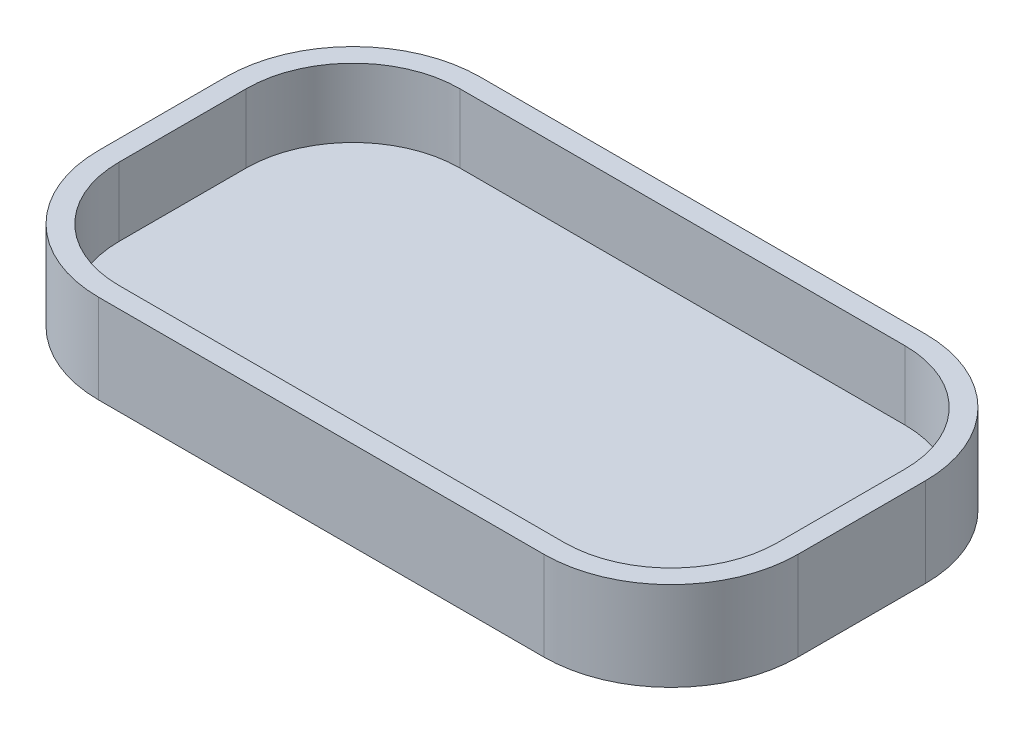
SolidWorks part; units mm, degrees
material "Kujná litina (temperovaná)"
ref_plane "Přední rovina" through (0, 0, 0) normal (0, 0, 1) x (1, 0, 0)
ref_plane "Horní rovina" through (0, 0, 0) normal (0, 1, 0) x (1, 0, 0)
ref_plane "Pravá rovina" through (0, 0, 0) normal (1, 0, 0) x (0, 0, -1)
sketch "Skica1" plane through (0, 0, 0) normal (0, 1, 0) x (1, 0, 0)
  line L1 (0, 0) -> (-55, 0)
  line L2 (0, 0) -> (0, 30)
  line L3 (0, 30) -> (-55, 30)
  line L4 (-55, 0) -> (-55, 30)
  point P7 (-52.8261, 33.8351)
  dimension "D1" = 55
  dimension "D2" = 30
extrude "Přidat vysunutím1" add sketch "Skica1" along normal blind 7
fillet "Zaoblit1" radius 10 4 edges at (0, 3.5, -30) (0, 3.5, 0) (-55, 3.5, -30) (-55, 3.5, 0)
shell "Skořepina1" thickness 1.6
